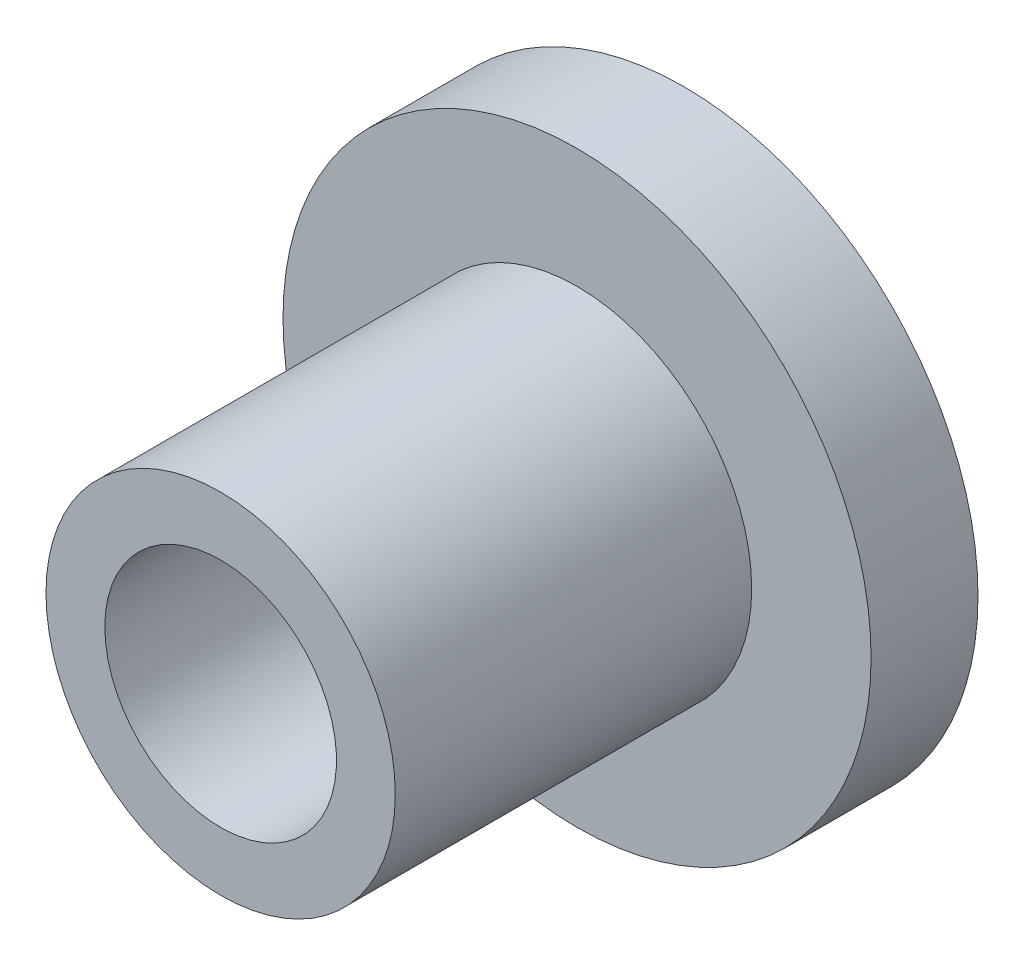
SolidWorks part; units mm, degrees
ref_plane "Front Plane" through (0, 0, 0) normal (0, 0, 1) x (1, 0, 0)
ref_plane "Top Plane" through (0, 0, 0) normal (0, 1, 0) x (1, 0, 0)
ref_plane "Right Plane" through (0, 0, 0) normal (1, 0, 0) x (0, 0, -1)
sketch "Sketch1" plane through (0, 0, 0) normal (0, 0, 1) x (1, 0, 0)
  circle A0 centre (0, 0) radius 3.25
  circle A2 centre (0, 0) radius 8.25
  dimension "D1" = 6.5
  dimension "D2" = 16.5
extrude "Boss-Extrude1" add sketch "Sketch1" along normal blind 13
sketch "Sketch2" plane through (0, 0, 0) normal (0, 0, -1) x (-1, 0, 0)
  circle A0 centre (0, 0) radius 4.9
  dimension "D1" = 9.8
extrude "Cut-Extrude-Thin1" cut sketch "Sketch2" against normal blind 13 from offset 3 thin offset against normal yes
equation "\"D2@Sketch1\"=\"D1@Sketch1\"+2*5"
